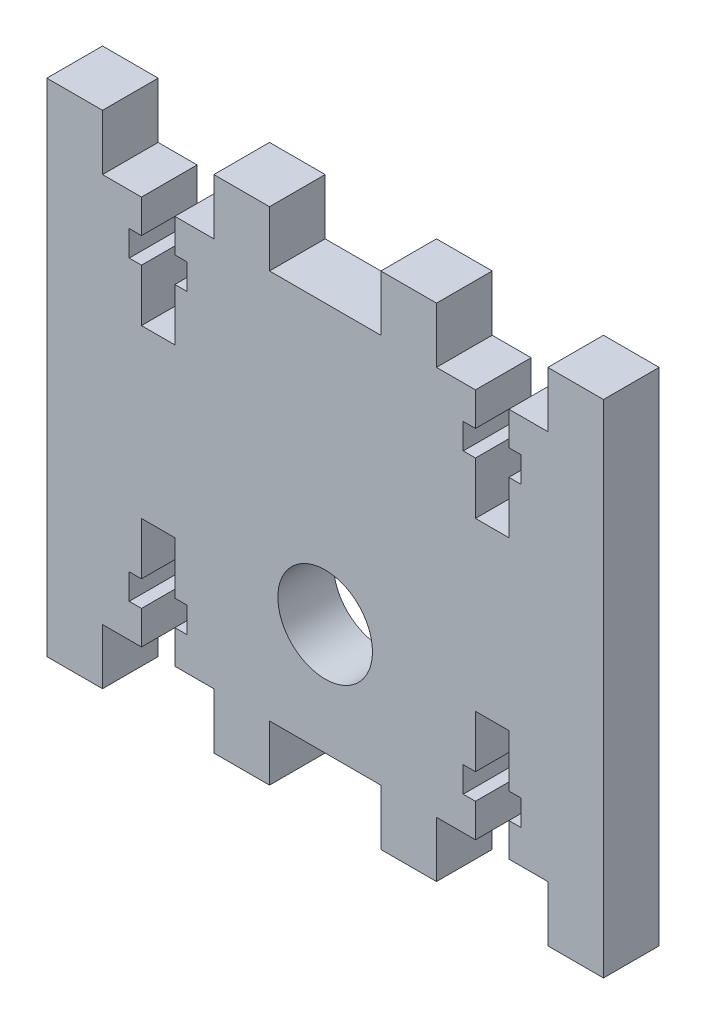
SolidWorks part; units mm, degrees
ref_plane "Plan de face" through (0, 0, 0) normal (0, 0, 1) x (1, 0, 0)
ref_plane "Plan de dessus" through (0, 0, 0) normal (0, 1, 0) x (1, 0, 0)
ref_plane "Plan de droite" through (0, 0, 0) normal (1, 0, 0) x (0, 0, -1)
sketch "Esquisse1" plane through (0, 0, 0) normal (0, 0, 1) x (1, 0, 0)
  line L0 (-10, 17.5) -> (-10, -17.5)
  line L2 (10, 17.5) -> (10, -17.5) construction
  line L3 (10, 17.5) -> (20, 17.5)
  line L4 (10, -17.5) -> (20, -17.5)
  line L5 (15, -17.5) -> (15, 17.5) construction
  line L6 (40, 17.5) -> (40, -17.5)
  line L7 (0, 7.5) -> (0, -7.5) construction
  circle A0 centre (15, -7.5) radius 4.25
  point P4 (15, -6.7976)
  point P14 (0, 0)
  point P15 (24.0459, 0)
  point P18 (0, 0)
  line B0 (-2.6, -14.5) -> (-2.6, -12.2)
  line B1 (1.5, -12.2) -> (1.5, -7.5)
  line B2 (-1.5, -7.5) -> (-1.5, -12.2)
  line B3 (-2.6, -12.2) -> (-1.5, -12.2)
  line B4 (0, -17.5) -> (0, -6.2792) construction
  line B5 (-1.5, -17.5) -> (-5, -17.5)
  line B6 (-5, -22.5) -> (-10, -22.5)
  line B7 (-10, -22.5) -> (-10, -17.5)
  line B8 (-5, -22.5) -> (-5, -17.5)
  line B9 (1.5, -17.5) -> (5, -17.5)
  line B10 (5, -17.5) -> (5, -22.5)
  line B11 (5, -22.5) -> (10, -22.5)
  line B12 (10, -22.5) -> (10, -17.5)
  line B13 (-1.5, -17.5) -> (1.5, -17.5) construction
  line B14 (1.5, -17.5) -> (1.5, -14.5)
  line B15 (1.5, -12.2) -> (2.6, -12.2)
  line B16 (2.6, -14.5) -> (1.5, -14.5)
  line B17 (1.5, -7.5) -> (-1.5, -7.5)
  line B18 (-1.5, -14.5) -> (-2.6, -14.5)
  line B19 (2.6, -12.2) -> (2.6, -14.5)
  line B20 (-1.5, -14.5) -> (-1.5, -17.5)
  line B21 (0, -7.5) -> (0, -17.5) construction
  line B22 (-2.6, 14.5) -> (-2.6, 12.2)
  line B23 (1.5, 12.2) -> (1.5, 7.5)
  line B24 (-1.5, 7.5) -> (-1.5, 12.2)
  line B25 (-2.6, 12.2) -> (-1.5, 12.2)
  line B26 (0, 17.5) -> (0, 6.2792) construction
  line B27 (-1.5, 17.5) -> (-5, 17.5)
  line B28 (-5, 22.5) -> (-10, 22.5)
  line B29 (-10, 22.5) -> (-10, 17.5)
  line B30 (-5, 22.5) -> (-5, 17.5)
  line B31 (1.5, 17.5) -> (5, 17.5)
  line B32 (5, 17.5) -> (5, 22.5)
  line B33 (5, 22.5) -> (10, 22.5)
  line B34 (10, 22.5) -> (10, 17.5)
  line B35 (-1.5, 17.5) -> (1.5, 17.5) construction
  line B36 (1.5, 17.5) -> (1.5, 14.5)
  line B37 (1.5, 12.2) -> (2.6, 12.2)
  line B38 (2.6, 14.5) -> (1.5, 14.5)
  line B39 (1.5, 7.5) -> (-1.5, 7.5)
  line B40 (-1.5, 14.5) -> (-2.6, 14.5)
  line B41 (2.6, 12.2) -> (2.6, 14.5)
  line B42 (-1.5, 14.5) -> (-1.5, 17.5)
  line B43 (0, 7.5) -> (0, 17.5) construction
  line B44 (32.6, 14.5) -> (32.6, 12.2)
  line B45 (28.5, 12.2) -> (28.5, 7.5)
  line B46 (31.5, 7.5) -> (31.5, 12.2)
  line B47 (32.6, 12.2) -> (31.5, 12.2)
  line B48 (30, 17.5) -> (30, 6.2792) construction
  line B49 (31.5, 17.5) -> (35, 17.5)
  line B50 (35, 22.5) -> (40, 22.5)
  line B51 (40, 22.5) -> (40, 17.5)
  line B52 (35, 22.5) -> (35, 17.5)
  line B53 (28.5, 17.5) -> (25, 17.5)
  line B54 (25, 17.5) -> (25, 22.5)
  line B55 (25, 22.5) -> (20, 22.5)
  line B56 (20, 22.5) -> (20, 17.5)
  line B57 (31.5, 17.5) -> (28.5, 17.5) construction
  line B58 (28.5, 17.5) -> (28.5, 14.5)
  line B59 (28.5, 12.2) -> (27.4, 12.2)
  line B60 (27.4, 14.5) -> (28.5, 14.5)
  line B61 (28.5, 7.5) -> (31.5, 7.5)
  line B62 (31.5, 14.5) -> (32.6, 14.5)
  line B63 (27.4, 12.2) -> (27.4, 14.5)
  line B64 (31.5, 14.5) -> (31.5, 17.5)
  line B65 (30, 7.5) -> (30, 17.5) construction
  line B66 (32.6, -14.5) -> (32.6, -12.2)
  line B67 (28.5, -12.2) -> (28.5, -7.5)
  line B68 (31.5, -7.5) -> (31.5, -12.2)
  line B69 (32.6, -12.2) -> (31.5, -12.2)
  line B70 (30, -17.5) -> (30, -6.2792) construction
  line B71 (31.5, -17.5) -> (35, -17.5)
  line B72 (35, -22.5) -> (40, -22.5)
  line B73 (40, -22.5) -> (40, -17.5)
  line B74 (35, -22.5) -> (35, -17.5)
  line B75 (28.5, -17.5) -> (25, -17.5)
  line B76 (25, -17.5) -> (25, -22.5)
  line B77 (25, -22.5) -> (20, -22.5)
  line B78 (20, -22.5) -> (20, -17.5)
  line B79 (31.5, -17.5) -> (28.5, -17.5) construction
  line B80 (28.5, -17.5) -> (28.5, -14.5)
  line B81 (28.5, -12.2) -> (27.4, -12.2)
  line B82 (27.4, -14.5) -> (28.5, -14.5)
  line B83 (28.5, -7.5) -> (31.5, -7.5)
  line B84 (31.5, -14.5) -> (32.6, -14.5)
  line B85 (27.4, -12.2) -> (27.4, -14.5)
  line B86 (31.5, -14.5) -> (31.5, -17.5)
  line B87 (30, -7.5) -> (30, -17.5) construction
  dimension "D2" = 8.5
  dimension "D1" = 35
  dimension "D3" = 10
  dimension "D4" = 10
sketch_block_instance "Insert M3 plots ep 5mm-1"
sketch_block "Insert M3 plots ep 5mm" parameters "D1"=10, "D2"=5, "D3"=5
sketch_block_instance "Decoupe Insert M3-4"
sketch_block "Decoupe Insert M3" parameters "D1"=5.2, "D2"=3, "D3"=2.3, "D4"=3, "D5"=10
sketch_block_instance "Insert M3 plots ep 5mm-3"
sketch_block_instance "Insert M3 plots ep 5mm-4"
sketch_block_instance "Insert M3 plots ep 5mm-5"
extrude "Boss.-Extru.1" add sketch "Esquisse1" along normal blind 5
